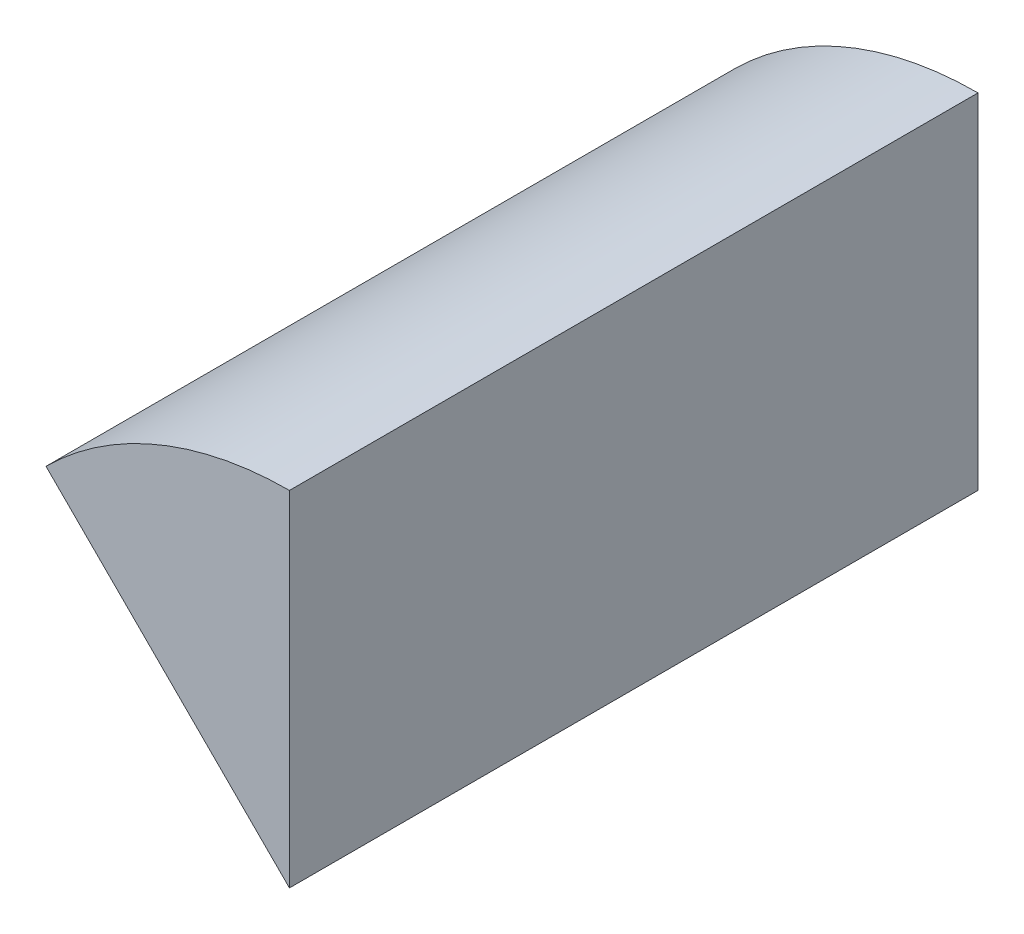
SolidWorks part; units mm, degrees
ref_plane "Alzado" through (0, 0, 0) normal (0, 0, 1) x (1, 0, 0)
ref_plane "Planta" through (0, 0, 0) normal (0, 1, 0) x (1, 0, 0)
ref_plane "Vista lateral" through (0, 0, 0) normal (1, 0, 0) x (0, 0, -1)
sketch "Croquis1" plane through (0, 0, 0) normal (0, 0, 1) x (1, 0, 0)
  line L0 (0, 25) -> (0, 0)
  line L2 (0, 0) -> (-17.6777, 17.6777)
  arc A0 (0, 25) -> (-17.6777, 17.6777) centre (0, 0) ccw
  dimension "D1" = 50
extrude "Saliente-Extruir1" add sketch "Croquis1" along normal blind 50
sketch "Croquis2" plane through (0, 0, 0) normal (0, 0, -1) x (-1, 0, 0)
  circle A0 centre (6.5944, 16.7415) radius 5
  dimension "D1" = 10
extrude "Cortar-Extruir1" cut sketch "Croquis2" against normal blind 10
